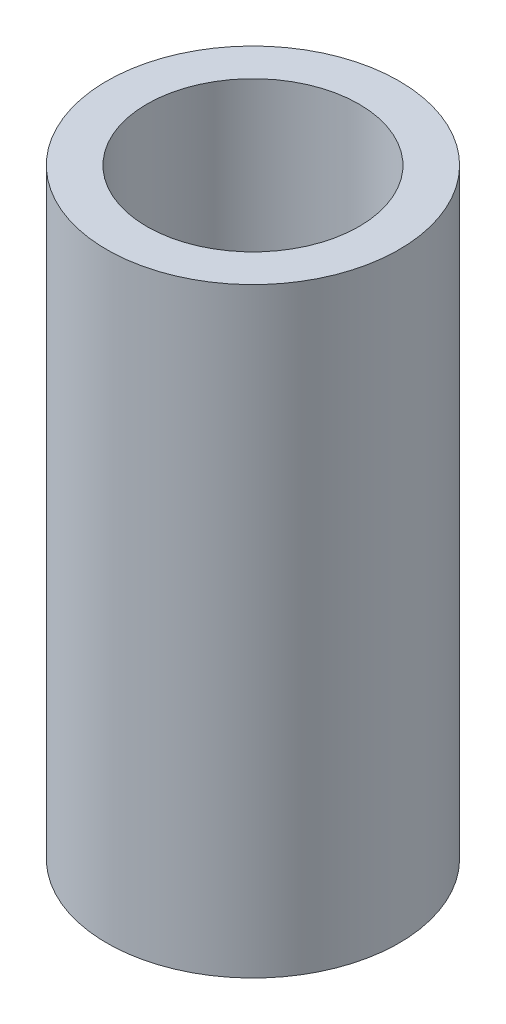
SolidWorks part; units mm, degrees
ref_plane "Front Plane" through (0, 0, 0) normal (0, 0, 1) x (1, 0, 0)
ref_plane "Top Plane" through (0, 0, 0) normal (0, 1, 0) x (1, 0, 0)
ref_plane "Right Plane" through (0, 0, 0) normal (1, 0, 0) x (0, 0, -1)
sketch "Sketch1" plane through (0, 0, 0) normal (0, 0, 1) x (1, 0, 0)
  line L0 (13.462, 0) -> (18.542, 0)
  line L1 (18.542, 0) -> (18.542, -76.2)
  line L2 (18.542, -76.2) -> (0, -76.2)
  line L3 (0, -76.2) -> (0, -44.45) construction
  line L4 (0, -44.45) -> (13.462, -44.45)
  line L5 (13.462, -44.45) -> (13.462, 0)
  line L6 (0, -76.2) -> (0, -44.45)
  point P3 (0, 0)
  point P8 (0, 0)
  point P9 (13.462, -32.3895)
  dimension "D1" = 26.924
  dimension "D2" = 5.08
  dimension "D3" = 44.45
  dimension "D4" = 76.2
revolve "Revolve1" add sketch "Sketch1" angle 360 about L3
